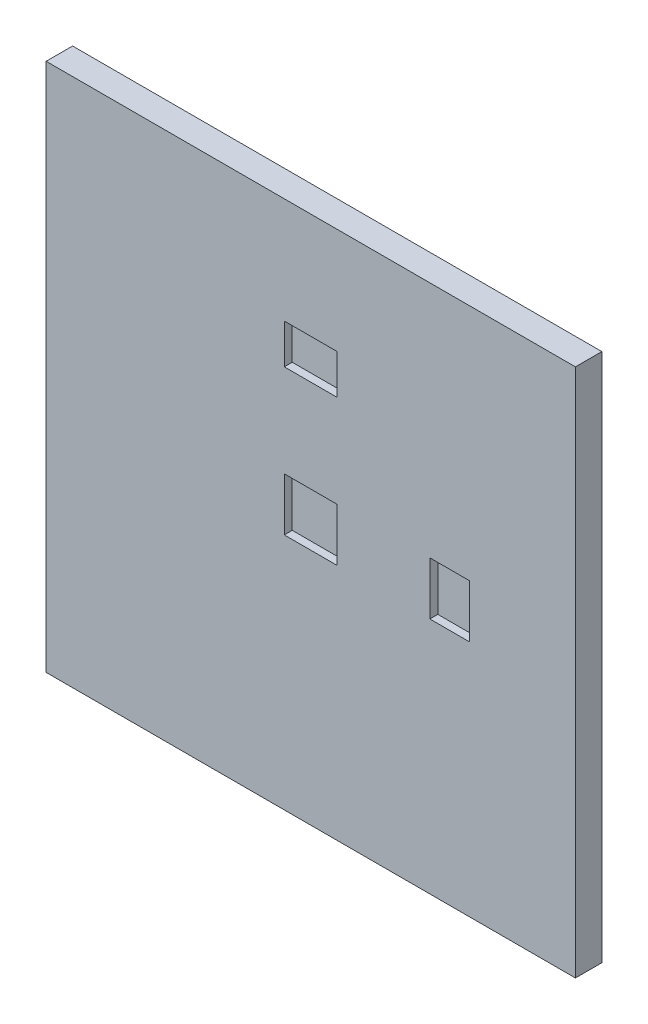
SolidWorks part; units mm, degrees
ref_plane "Ön Düzlem" through (0, 0, 0) normal (0, 0, 1) x (1, 0, 0)
ref_plane "Üst Düzlem" through (0, 0, 0) normal (0, 1, 0) x (1, 0, 0)
ref_plane "Sağ Düzlem" through (0, 0, 0) normal (1, 0, 0) x (0, 0, -1)
sketch "Sketch1" plane through (0, 0, 0) normal (0, 0, 1) x (1, 0, 0)
  line L1 (0, 0) -> (-200, 0)
  line L2 (0, 0) -> (0, -200)
  line L3 (0, -200) -> (-200, -200)
  line L4 (-200, 0) -> (-200, -200)
  dimension "D1" = 200
  dimension "D2" = 200
extrude "Boss-Extrude1" add sketch "Sketch1" along normal blind 10
sketch "Sketch2" plane through (0, 0, 10) normal (0, 0, 1) x (1, 0, 0)
  line L0 (-200, 0) -> (-200, -200) construction
  line L1 (-110, -90) -> (-90, -90)
  line L2 (-110, -90) -> (-110, -110)
  line L3 (-110, -110) -> (-90, -110)
  line L4 (-90, -90) -> (-90, -110)
  line L5 (-200, -200) -> (0, -200) construction
  dimension "D1" = 20
  dimension "D2" = 20
  dimension "D3" = 90
  dimension "D4" = 90
sketch "Sketch3" plane through (0, 0, 10) normal (0, 0, 1) x (1, 0, 0)
  line L0 (0, -200) -> (0, 0) construction
  line L1 (-110, -40) -> (-90, -40)
  line L2 (-110, -40) -> (-110, -55)
  line L3 (-110, -55) -> (-90, -55)
  line L4 (-90, -40) -> (-90, -55)
  line L5 (0, 0) -> (-200, 0) construction
  line L6 (-200, -200) -> (0, -200) construction
  line L11 (-55, -90) -> (-40, -90)
  line L12 (-55, -90) -> (-55, -110)
  line L13 (-55, -110) -> (-40, -110)
  line L14 (-40, -90) -> (-40, -110)
  dimension "D1" = 20
  dimension "D2" = 15
  dimension "D3" = 90
  dimension "D4" = 40
  dimension "D5" = 15
  dimension "D6" = 20
  dimension "D7" = 40
  dimension "D8" = 90
extrude "Cut-Extrude2" cut sketch "Sketch2" against normal blind 3
extrude "Cut-Extrude3" cut sketch "Sketch3" against normal blind 3
